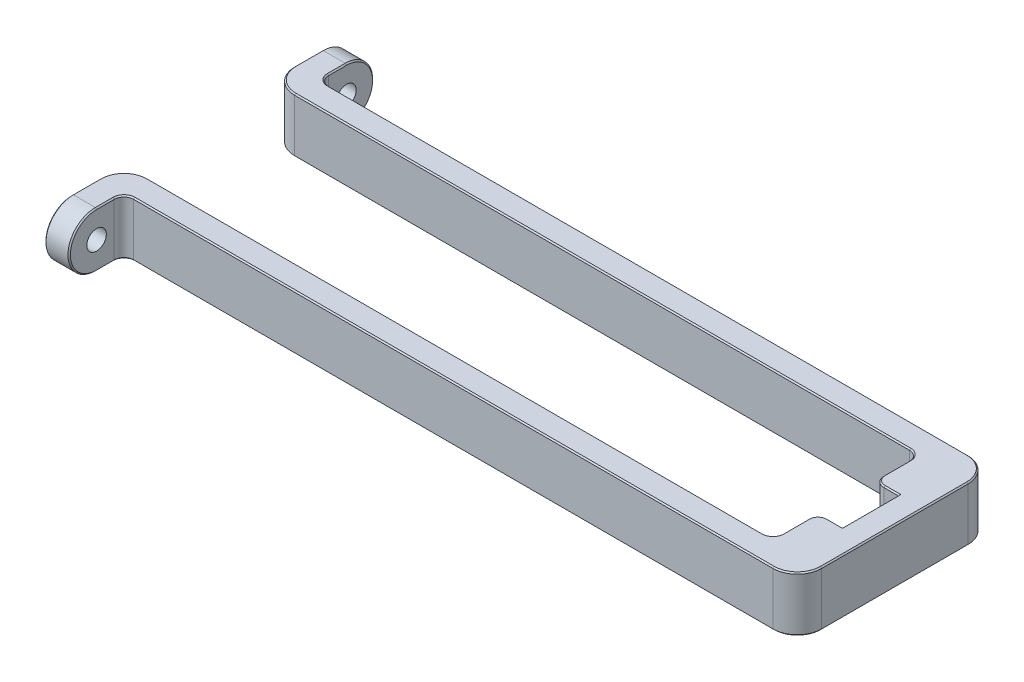
SolidWorks part; units mm, degrees
material "ABS"
ref_plane "前视基准面" through (0, 0, 0) normal (0, 0, 1) x (1, 0, 0)
ref_plane "上视基准面" through (0, 0, 0) normal (0, 1, 0) x (1, 0, 0)
ref_plane "右视基准面" through (0, 0, 0) normal (1, 0, 0) x (0, 0, -1)
sketch "草图1" plane through (0, 0, 0) normal (0, 1, 0) x (1, 0, 0)
  line L0 (0, 0) -> (0, 24)
  line L1 (0, 24) -> (106.5, 24)
  line L2 (106.5, 24) -> (106.5, 16.6)
  line L3 (106.5, 0) -> (0, 0)
  line L4 (110.5, -4) -> (0, -4)
  line L6 (0, 28) -> (110.5, 28)
  line L7 (110.5, 28) -> (110.5, -4)
  line L8 (0, 24) -> (0, 28)
  line L9 (0, 0) -> (0, -4)
  line L10 (-4, 28) -> (110.5, 28) construction
  line L11 (-4, -4) -> (-4, 28) construction
  line L12 (110.5, -4) -> (-4, -4) construction
  line L13 (110.5, 28) -> (114.5, 28)
  line L14 (114.5, 28) -> (114.5, 16.6)
  line L15 (114.5, 16.6) -> (110.5, 16.6)
  line L16 (110.5, 12) -> (0, 12) construction
  line L17 (114.5, 7.4) -> (110.5, 7.4)
  line L18 (114.5, -4) -> (114.5, 7.4)
  line L19 (110.5, -4) -> (114.5, -4)
  line L20 (114.5, 16.6) -> (114.5, 7.4)
  line L21 (110.5, 16.6) -> (106.5, 16.6)
  line L22 (110.5, 7.4) -> (106.5, 7.4)
  line L23 (106.5, 7.4) -> (106.5, 0)
  line L24 (106.5, 24) -> (106.5, 0) construction
  dimension "D1" = 106.5
  dimension "D2" = 24
  dimension "D4" = 9.2
  dimension "D5" = 4
  dimension "D3" = 4
extrude "凸台-拉伸1" add sketch "草图1" along normal blind 9 contours L3 L9 L4 L7 L6 L8 L1 L2 | L15 L14 L13 L7 | L7 L19 L18 L17 | L22 L23 L3 L9 L4 L7 | L20 L15 L7 L17
sketch "草图2" plane through (0, 0, 0) normal (-1, 0, 0) x (0, 0, 1)
  line L0 (0, 4.5) -> (4, 4.5) construction
  line L1 (0, 9) -> (0, 0) construction
  line L2 (4, 9) -> (4, 0) construction
  line L3 (8.5, 4.5) -> (4, 4.5) construction
  line L4 (4, 9) -> (8.5, 9)
  line L5 (8.5, 0) -> (4, 0)
  line L6 (-32.5, 4.5) -> (-28, 4.5) construction
  line L7 (0, 9) -> (4, 9) construction
  line L8 (-32.5, 0) -> (-28, 0)
  line L9 (-12, 9) -> (-12, 0) construction
  line L10 (-28, 9) -> (-32.5, 9)
  line L11 (-28, 9) -> (-28, 0)
  line L16 (4, 9) -> (4, 0)
  line L18 (-16.6, 9) -> (-7.4, 9) construction
  line L19 (-16.6, 0) -> (-7.4, 0) construction
  circle A0 centre (8.5, 4.5) radius 4.5
  circle A1 centre (8.5, 4.5) radius 1.6
  circle A2 centre (-32.5, 4.5) radius 1.6
  circle A3 centre (-32.5, 4.5) radius 4.5
  dimension "D1" = 9
  dimension "D2" = 3.2
extrude "凸台-拉伸2" add sketch "草图2" against normal blind 4
fillet "圆角1" radius 4 4 edges at (0, 4.5, 0) (0, 4.5, -24) (114.5, 4.5, -28) (114.5, 4.5, 4)
fillet "圆角2" radius 1.6 6 edges at (4, 4.5, 4) (4, 4.5, -28) (106.5, 4.5, -24) (106.5, 4.5, -7.4) (106.5, 4.5, -16.6) (106.5, 4.5, 0)
chamfer "倒角1" distance 0.2 angle 45 52 edges at (0, 0, -30.25) (1.1716, 0, -25.1716) (54.45, 0, -24) (106.0314, 0, -23.5314) (106.5, 0, -20.3) (54.45, 0, 0) (1.1716, 0, 1.1716) (0, 0, 6.25) (4.4686, 0, -28.4686) (58.05, 0, -28) (113.3284, 0, -26.8284) (110.5, 0, -12) (4.4686, 0, 4.4686) (58.05, 0, 4) (113.3284, 0, 2.8284) (114.5, 0, -12) (0, 4.5, 13) (4, 4.5, 13) (0, 4.5, -37) (4, 4.5, -37) (0, 9, 6.25) (1.1716, 9, 1.1716) (54.45, 9, 0) (106.5, 9, -20.3) (106.0314, 9, -23.5314) (54.45, 9, -24) (1.1716, 9, -25.1716) (0, 9, -30.25) (4.4686, 9, 4.4686) (58.05, 9, 4) (113.3284, 9, 2.8284) (4.4686, 9, -28.4686) (58.05, 9, -28) (113.3284, 9, -26.8284) (110.5, 9, -12) (114.5, 9, -12) (106.5, 0, -3.7) (109.3, 0, -7.4) (109.3, 0, -16.6) (4, 0, 7.05) (4, 9, 7.05) (106.5, 9, -3.7) (109.3, 9, -7.4) (109.3, 9, -16.6) (4, 0, -31.05) (4, 9, -31.05) (106.0314, 0, -0.4686) (106.9686, 0, -17.0686) (106.9686, 0, -6.9314) (106.9686, 9, -17.0686) (106.0314, 9, -0.4686) (106.9686, 9, -6.9314)
